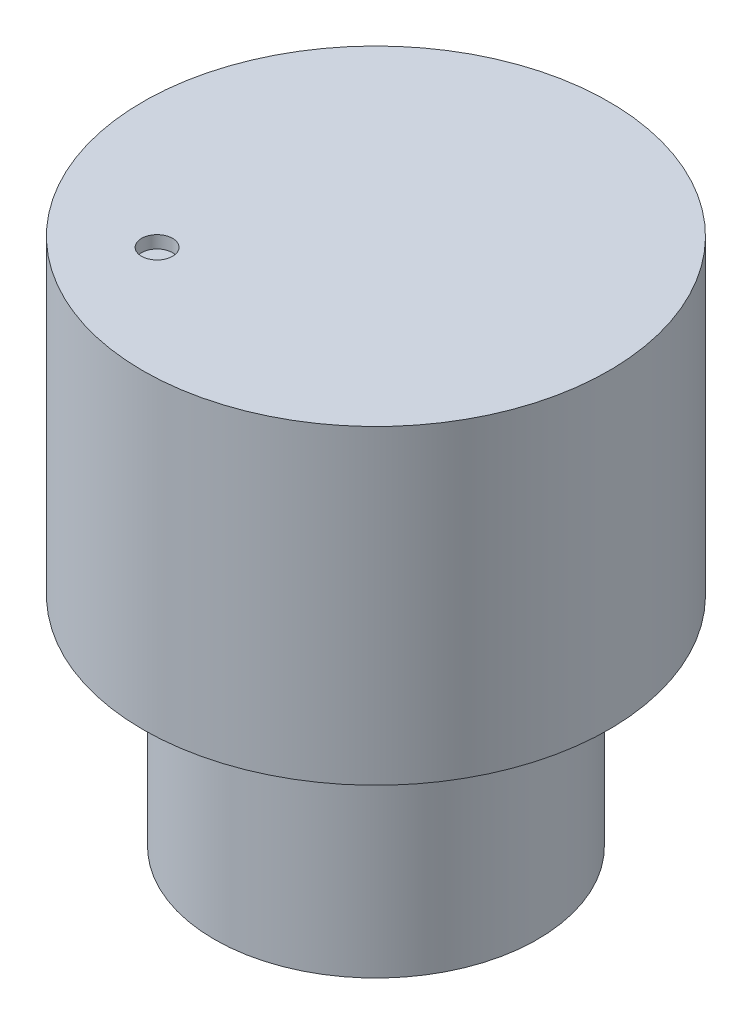
SolidWorks part; units mm, degrees
ref_plane "Front Plane" through (0, 0, 0) normal (0, 0, 1) x (1, 0, 0)
ref_plane "Top Plane" through (0, 0, 0) normal (0, 1, 0) x (1, 0, 0)
ref_plane "Right Plane" through (0, 0, 0) normal (1, 0, 0) x (0, 0, -1)
sketch "Sketch1" plane through (0, 0, 0) normal (0, 1, 0) x (1, 0, 0)
  circle A0 centre (0, 0) radius 3.2
  circle A1 centre (0, 0) radius 5.2
  dimension "D1" = 6.4
  dimension "D2" = 2
extrude "Boss-Extrude1" add sketch "Sketch1" along normal blind 7
sketch "Sketch2" plane through (0, 7, 0) normal (0, 1, 0) x (1, 0, 0)
  circle A0 centre (0, 0) radius 7.5
  dimension "D1" = 15
extrude "Boss-Extrude2" add sketch "Sketch2" along normal blind 10
sketch "Sketch3" plane through (0, 7, 0) normal (0, -1, 0) x (1, 0, 0)
  line L1 (-3.2, 0.4) -> (3.2, 0.4)
  line L2 (-3.2, 0.4) -> (-3.2, -0.4)
  line L3 (-3.2, -0.4) -> (3.2, -0.4)
  line L4 (3.2, 0.4) -> (3.2, -0.4)
  line L5 (-3.2, 0.4) -> (3.2, -0.4) construction
  line L6 (-3.2, -0.4) -> (3.2, 0.4) construction
  circle A1 centre (0, 0) radius 3.2
  circle A2 centre (0, 0) radius 3.2
  point P0 (0, 0)
  circle M5 centre (0, 0) radius 3.2
  dimension "D2" = 0.8
  dimension "D1" = 0
extrude "Boss-Extrude3" add sketch "Sketch3" along normal blind 1 contours L3 L1 M5
sketch "Sketch4" plane through (0, 7, 0) normal (0, -1, 0) x (1, 0, 0)
  line L0 (-2.6458, -1.8) -> (2.6458, -1.8)
  line L1 (3.1749, -0.4) -> (-3.1749, -0.4)
  line L2 (3.1749, -0.4) -> (-3.1749, -0.4)
  arc A1 (-3.1749, -0.4) -> (3.1749, -0.4) centre (0, 0) ccw
  arc A2 (-3.1749, -0.4) -> (3.1749, -0.4) centre (0, 0) ccw
  arc A3 (3.1749, 0.4) -> (-3.1749, 0.4) centre (0, 0) ccw construction
  point P7 (0, 3.2)
  arc M5 (-3.1749, -0.4) -> (3.1749, -0.4) centre (0, 0) ccw
  dimension "D2" = 5
  dimension "D1" = 0
extrude "Boss-Extrude4" add sketch "Sketch4" along normal blind 5 contours L0 M5
sketch "Sketch5" plane through (0, 17, 0) normal (0, 1, 0) x (1, 0, 0)
  line L0 (-2.6458, 1.8) -> (2.6458, 1.8) construction
  line L1 (-2.6458, 1.8) -> (2.6458, 1.8) construction
  line L2 (0, 1.8) -> (0, -7.5) construction
  line L3 (-3.2139, -3.8302) -> (0, 0) construction
  circle A0 centre (-3.2139, -3.8302) radius 0.5
  circle A1 centre (0, 0) radius 7.5 construction
  dimension "D3" = 1
  dimension "D1" = 40
  dimension "D2" = 5
extrude "Cut-Extrude1" cut sketch "Sketch5" against normal blind 0.4
